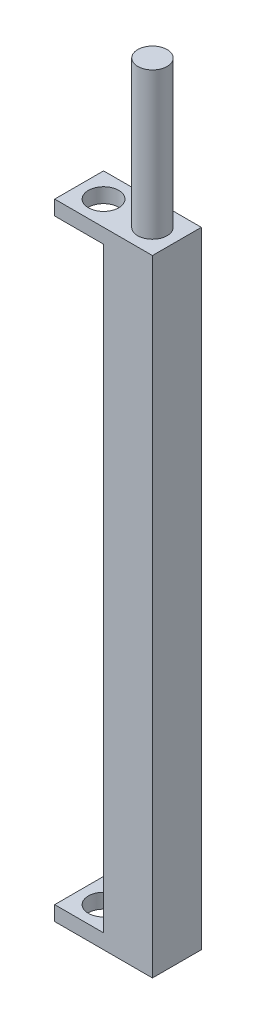
SolidWorks part; units mm, degrees
ref_plane "前视基准面" through (0, 0, 0) normal (0, 0, 1) x (1, 0, 0)
ref_plane "上视基准面" through (0, 0, 0) normal (0, 1, 0) x (1, 0, 0)
ref_plane "右视基准面" through (0, 0, 0) normal (1, 0, 0) x (0, 0, -1)
other "Configuration Table"
sketch "草图2" plane through (0, 0, 0) normal (0, 1, 0) x (1, 0, 0)
  line L1 (5, -2.5) -> (-5, -2.5)
  line L2 (5, -2.5) -> (5, 2.5)
  line L3 (5, 2.5) -> (-5, 2.5)
  line L4 (-5, -2.5) -> (-5, 2.5)
  line L5 (5, -2.5) -> (-5, 2.5) construction
  line L6 (5, 2.5) -> (-5, -2.5) construction
  circle A0 centre (2.5, 0) radius 1.55
  circle A1 centre (-2.5, 0) radius 1.55
  point P0 (0, 0)
  dimension "D3" = 3.1
  dimension "D4" = 3.1
  dimension "D1" = 10
  dimension "D2" = 2.5
  dimension "D5" = 2.5
  dimension "D6" = 5
extrude "凸台-拉伸1" add sketch "草图2" along normal blind 1.5 contours L3 L4 L1 L2
sketch "草图3" plane through (0, 0, 0) normal (0, -1, 0) x (1, 0, 0)
  line L0 (5, -2.5) -> (-5, -2.5) construction
  circle A0 centre (-2.5, 0) radius 1.55
  dimension "D3" = 3.1
  dimension "D1" = 2.5
  dimension "D2" = 2.5
extrude "切除-拉伸1" cut sketch "草图3" against normal blind 1.5
sketch "草图4" plane through (0, 0, 0) normal (0, -1, 0) x (1, 0, 0)
  line L0 (0, 2.5) -> (0, -2.5)
  line L1 (5, 2.5) -> (-5, 2.5) construction
  line L2 (5, -2.5) -> (-5, -2.5) construction
  line L3 (0, -2.5) -> (5, -2.5)
  line L4 (5, -2.5) -> (5, 2.5)
  line L5 (5, 2.5) -> (0, 2.5)
  dimension "D1" = 5
extrude "凸台-拉伸2" add sketch "草图4" along normal blind 61
sketch "草图5" plane through (0, -61, 0) normal (0, -1, 0) x (1, 0, 0)
  line L1 (5, 2.5) -> (-5, 2.5)
  line L2 (5, 2.5) -> (5, -2.5)
  line L3 (5, -2.5) -> (-5, -2.5)
  line L4 (-5, 2.5) -> (-5, -2.5)
extrude "凸台-拉伸3" add sketch "草图5" along normal blind 1.5
sketch "草图6" plane through (0, -62.5, 0) normal (0, -1, 0) x (1, 0, 0)
  line L0 (-5, 2.5) -> (-5, -2.5) construction
  circle A0 centre (-2.5, 0) radius 1.55
  dimension "D2" = 3.1
  dimension "D1" = 2.5
extrude "切除-拉伸2" cut sketch "草图6" against normal blind 1.5
sketch "草图7" plane through (0, 1.5, 0) normal (0, 1, 0) x (1, 0, 0)
  line L0 (5, -2.5) -> (5, 2.5) construction
  line L1 (5, -2.5) -> (-5, -2.5) construction
  circle A0 centre (2.5, 0) radius 1.5
  dimension "D1" = 3
  dimension "D2" = 2.5
  dimension "D3" = 2.5
extrude "凸台-拉伸4" add sketch "草图7" along normal blind 15 contours A0
sketch "草图11" plane through (0, -62.5, 0) normal (0, -1, 0) x (1, 0, 0)
  line L0 (-5, -2.5) -> (5, -2.5) construction
  line L1 (5, -2.5) -> (5, 2.5) construction
  circle A0 centre (2.5, 0) radius 1.55
  dimension "D3" = 3.1
  dimension "D1" = 2.5
  dimension "D2" = 2.5
extrude "切除-拉伸3" cut sketch "草图11" against normal blind 10
